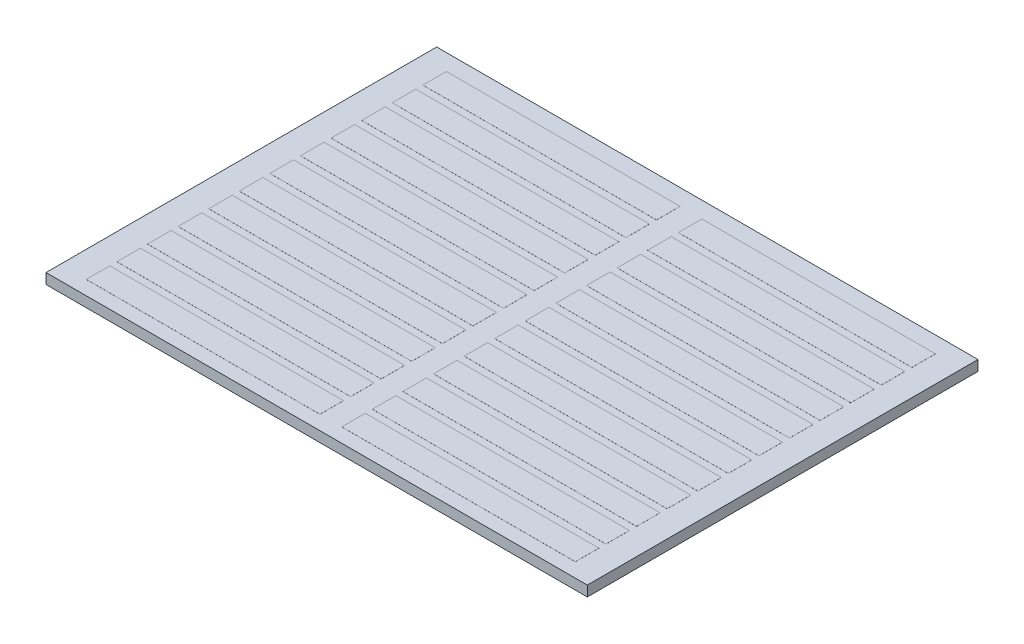
SolidWorks part; units mm, degrees
ref_plane "Спереди" through (0, 0, 0) normal (0, 0, 1) x (1, 0, 0)
ref_plane "Сверху" through (0, 0, 0) normal (0, 1, 0) x (1, 0, 0)
ref_plane "Справа" through (0, 0, 0) normal (1, 0, 0) x (0, 0, -1)
sketch "Эскиз1" plane through (0, 0, 0) normal (0, 1, 0) x (1, 0, 0)
  line L1 (-57.5, -41.5) -> (57.5, -41.5)
  line L2 (-57.5, -41.5) -> (-57.5, 41.5)
  line L3 (-57.5, 41.5) -> (57.5, 41.5)
  line L4 (57.5, -41.5) -> (57.5, 41.5)
  line L5 (-57.5, -41.5) -> (57.5, 41.5) construction
  line L6 (-57.5, 41.5) -> (57.5, -41.5) construction
  point P0 (0, 0)
  dimension "D1" = 83
  dimension "D2" = 115
extrude "Бобышка-Вытянуть1" add sketch "Эскиз1" along normal blind 2.2
sketch "Эскиз2" plane through (0, 2.2, 0) normal (0, 1, 0) x (1, 0, 0)
  line L0 (-57.5, 0) -> (57.5, 0) construction
  line L1 (2.3165, -38.4883) -> (51.945, -38.4883)
  line L2 (2.3165, -38.4883) -> (2.3165, -33.4883)
  line L3 (2.3165, -33.4883) -> (51.945, -33.4883)
  line L4 (51.945, -38.4883) -> (51.945, -33.4883)
  line L5 (2.3165, -38.4883) -> (51.945, -33.4883) construction
  line L6 (2.3165, -33.4883) -> (51.945, -38.4883) construction
  line L7 (-57.5, 41.5) -> (-57.5, -41.5) construction
  line L8 (57.5, -41.5) -> (57.5, 41.5) construction
  line L9 (0, -41.5) -> (0, 41.5) construction
  line L10 (-57.5, -41.5) -> (57.5, -41.5) construction
  line L11 (57.5, 41.5) -> (-57.5, 41.5) construction
  point P0 (27.1307, -35.9883)
  dimension "D1" = 5
extrude "Бобышка-Вытянуть2" add sketch "Эскиз2" along normal blind 0.01
pattern_linear "Линейный массив1" count 12 spacing 6.5 along (0, 0, -1) of "Бобышка-Вытянуть2"
mirror "Зеркальное отражение1" about plane through (0, 0, 0) normal (1, 0, 0) of "Линейный массив1", "Бобышка-Вытянуть2"
